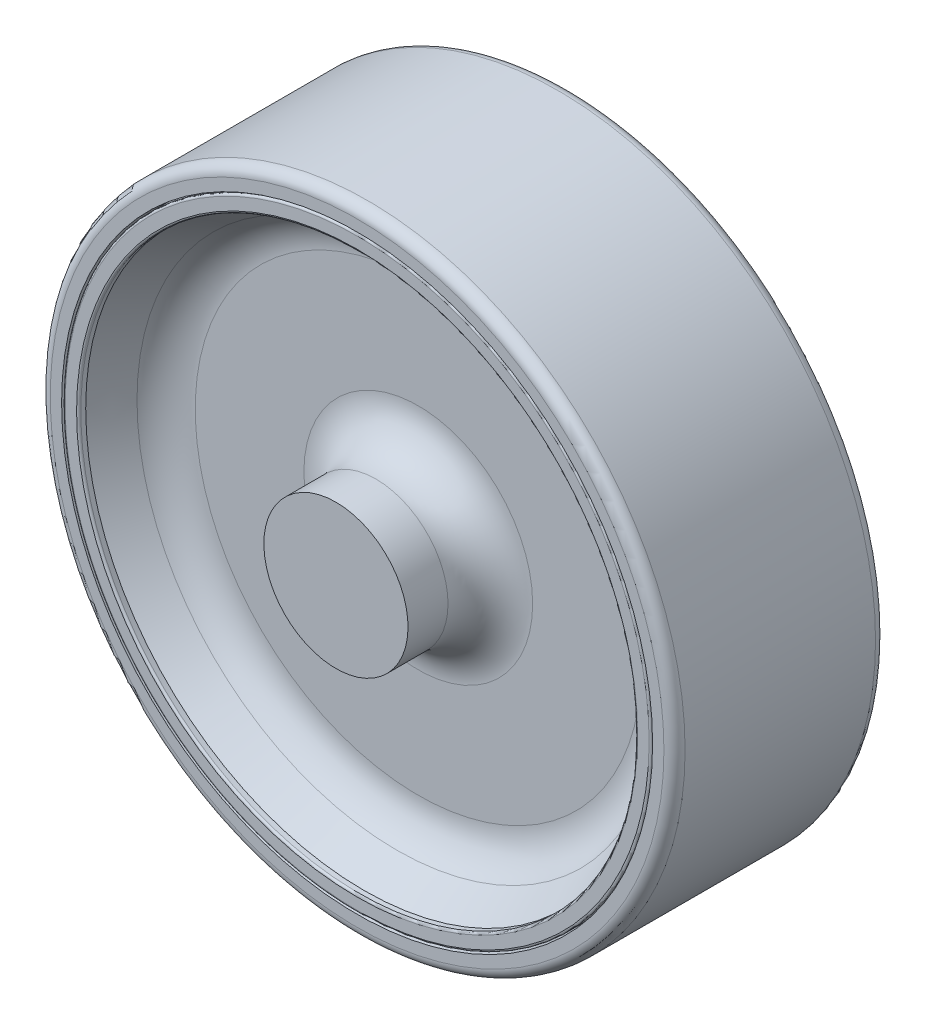
SolidWorks part; units mm, degrees
ref_plane "Front Plane" through (0, 0, 0) normal (0, 0, 1) x (1, 0, 0)
ref_plane "Top Plane" through (0, 0, 0) normal (0, 1, 0) x (1, 0, 0)
ref_plane "Right Plane" through (0, 0, 0) normal (1, 0, 0) x (0, 0, -1)
sketch "Sketch1" plane through (0, 0, 0) normal (0, 0, 1) x (1, 0, 0)
  circle A0 centre (0, 0) radius 150
  dimension "D1" = 300
extrude "Boss-Extrude1" add sketch "Sketch1" along normal blind 100
sketch "Sketch2" plane through (0, 0, 0) normal (1, 0, 0) x (0, 0, -1)
  line L0 (0, 0) -> (-129.1835, 0)
  line L1 (0, -150) -> (0, 150) construction
  line L2 (0, 131.5691) -> (-6.086, 131.5691)
  line L3 (0, 131.5691) -> (0, 27.1437)
  line L4 (-100, 131.5691) -> (-96.6802, 131.5691)
  line L5 (-100, 150) -> (-100, -150) construction
  line L6 (-6.086, 131.5691) -> (-55.1867, 117.0464)
  line L7 (-55.1867, 117.0464) -> (-55.1867, 34.0593)
  line L8 (-55.1867, 34.0593) -> (0, 27.1437)
  line L9 (-96.6802, 131.5691) -> (-71.0926, 117.0464)
  line L10 (-71.0926, 117.0464) -> (-71.0926, 34.0593)
  line L11 (-71.0926, 34.0593) -> (-100, 34.0593)
  line L12 (-100, 34.0593) -> (-100, 131.5691)
revolve "Cut-Revolve1" cut sketch "Sketch2" angle 360 about L0
fillet "Fillet1" radius 20 2 edges at (-117.0464, 0, 55.1867) (-34.0593, 0, 55.1867)
fillet "Fillet2" radius 20 2 edges at (-117.0464, 0, 71.0926) (-34.0593, 0, 71.0926)
sketch "Sketch4" plane through (0, 0, 0) normal (1, 0, 0) x (0, 0, -1)
  line L0 (0, 0) -> (5, 0)
  line L2 (-100, 34.0593) -> (-100, -34.0593) construction
  line L3 (-100, 0) -> (-110, 0)
  line L4 (-100, 0) -> (-100, 34.0593)
  line L6 (0, -27.1437) -> (0, 27.1437) construction
  line L7 (0, 27.1437) -> (5, 26.5171)
  line L8 (0, 0) -> (0, 27.1437)
  line L10 (5, 0) -> (5, 26.5171)
  line L11 (-100, 34.0593) -> (-110, 34.0593)
  line L12 (5, 0) -> (5, 37.0651) construction
  line L13 (0, 0) -> (0, 37.0651) construction
  line L14 (-110, 0) -> (-110, 34.0593)
  dimension "D2" = 10
  dimension "D1" = 5
revolve "Revolve1" add sketch "Sketch4" angle 360 about L3
fillet "Fillet3" radius 5 2 edges at (150, 0, 100) (150, 0, 0)
sketch "Sketch5" plane through (0, 0, -5) normal (0, 0, -1) x (-1, 0, 0)
  circle A0 centre (0, 0) radius 139.645
split line "Split Line1"
sketch "Sketch6" plane through (0, 0, -5) normal (0, 0, -1) x (-1, 0, 0)
  circle A1 centre (0, 0) radius 139.645
  circle A3 centre (0, 0) radius 139.0056
extrude "Cut-Extrude2" cut sketch "Sketch6" against normal blind 123
fillet "Fillet4" radius 1 1 edges at (139.645, 0, 0)
fillet "Fillet5" radius 1 2 edges at (139.0056, 0, 100) (-131.5691, 0, 100)
fillet "Fillet6" radius 1 2 edges at (139.0056, 0, 0) (-131.5691, 0, 0)
